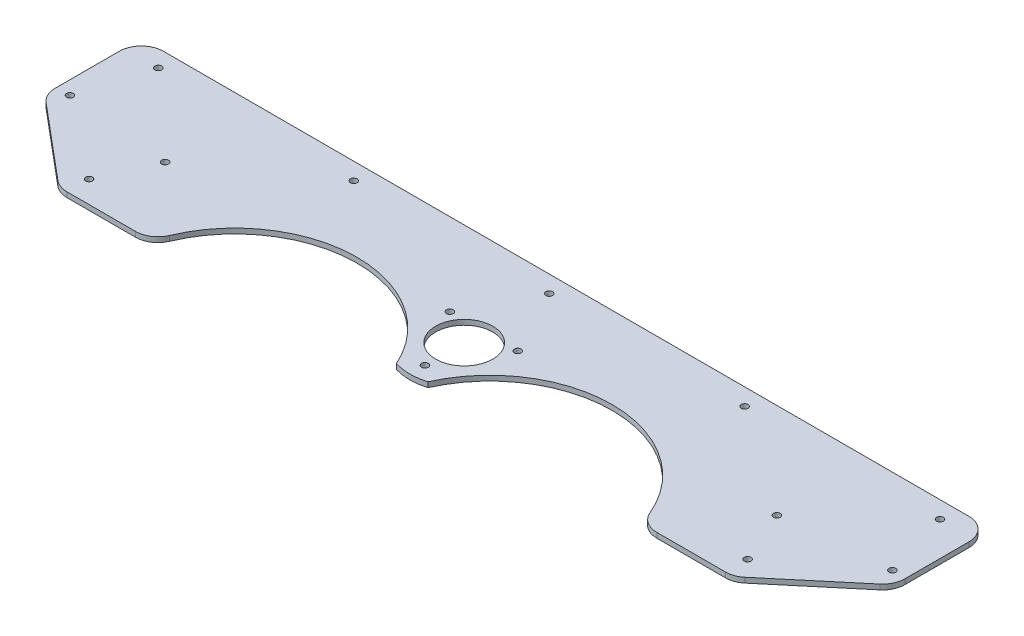
SolidWorks part; units mm, degrees
ref_plane "Plan de face" through (0, 0, 0) normal (0, 0, 1) x (1, 0, 0)
ref_plane "Plan de dessus" through (0, 0, 0) normal (0, 1, 0) x (1, 0, 0)
ref_plane "Plan de droite" through (0, 0, 0) normal (1, 0, 0) x (0, 0, -1)
sketch "Esquisse1" plane through (0, 0, 0) normal (0, 1, 0) x (1, 0, 0)
  line L0 (135, -20.0022) -> (99.25, -50)
  line L1 (0, 0) -> (135, 0)
  line L2 (0, 0) -> (0, -50)
  line L3 (0, -50) -> (135, -50)
  line L4 (135, 0) -> (135, -50)
  line L5 (125, 0) -> (125, -28.3932)
  dimension "D1" = 50
  dimension "D2" = 135
  dimension "D3" = 130
  dimension "D4" = 35.75
  dimension "D5" = 10
extrude "Boss.-Extru.1" add sketch "Esquisse1" along normal blind 1.5 contours L4 L1 L2 L3 L0
sketch "Esquisse2" plane through (0, 1.5, 0) normal (0, 1, 0) x (1, 0, 0)
  line L0 (0, -5) -> (57.5, -5) construction
  line L1 (57.5, -5) -> (115, -5) construction
  line L2 (135, 0) -> (135, -50) construction
  line L3 (125, -28.3932) -> (99.25, -50) construction
  line L4 (0, 0) -> (125, 0) construction
  line L5 (0, 0) -> (0, -50) construction
  line L6 (0, -50) -> (99.25, -50) construction
  circle A0 centre (0, -5) radius 1
  circle A1 centre (57.5, -5) radius 1
  circle A2 centre (115, -5) radius 1
  circle A3 centre (96.8842, -43.5) radius 1
  circle A4 centre (90, -28) radius 1
  circle A5 centre (121, -25) radius 1
  dimension "D2" = 2
  dimension "D4" = 6.5
  dimension "D1" = 20
  dimension "D3" = 5
  dimension "D5" = 6.5
  dimension "D6" = 22
  dimension "D7" = 3
  dimension "D8" = 31
  dimension "D9" = 90
extrude "Enlèv. mat.-Extru.1" cut sketch "Esquisse2" against normal through all
sketch "Esquisse4" plane through (0, 1.5, 0) normal (0, 1, 0) x (1, 0, 0)
  line L0 (0, -50) -> (99.25, -50) construction
  circle A0 centre (37.5, -60) radius 36
  dimension "D2" = 72
  dimension "D3" = 10
  dimension "D1" = 37.5
extrude "Enlèv. mat.-Extru.3" cut sketch "Esquisse4" against normal through all
fillet "Congé1" radius 6.5 4 edges at (99.25, 0.75, 50) (72.0832, 0.75, 50) (125, 0.75, 28.3932) (125, 0.75, 0)
mirror "Symétrie1" about plane through (0, 0, 0) normal (1, 0, 0) of bodies 105 102
sketch "Esquisse3" plane through (0, 1.5, 0) normal (0, 1, 0) x (1, 0, 0)
  line L0 (-99.25, -50) -> (99.25, -50) construction
  line L1 (-10, -24.2265) -> (0, -41.547) construction
  line L2 (0, -41.547) -> (10, -24.2265) construction
  line L3 (10, -24.2265) -> (-10, -24.2265) construction
  circle A0 centre (0, -30) radius 8.4
  circle A1 centre (0, -30) radius 5.7735 construction
  circle A2 centre (0, -41.547) radius 1
  circle A3 centre (-10, -24.2265) radius 1
  circle A4 centre (10, -24.2265) radius 1
  dimension "D1" = 16.8
  dimension "D2" = 2
  dimension "D3" = 20
  dimension "D4" = 20
extrude "Enlèv. mat.-Extru.2" cut sketch "Esquisse3" against normal blind 1.5
sketch "Esquisse5" plane through (0, 1.5, 0) normal (0, 1, 0) x (1, 0, 0)
  line L0 (7.7021, -44.0242) -> (7.7021, -51.9755)
  line L1 (7.7021, -51.9755) -> (-8.277, -51.9755)
  line L2 (-8.277, -51.9755) -> (-6.5005, -44.62)
  arc A0 (-6.5005, -44.62) -> (7.7021, -44.0242) centre (0, -30) ccw
  dimension "D1" = 32
extrude "Enlèv. mat.-Extru.4" cut sketch "Esquisse5" against normal through all
